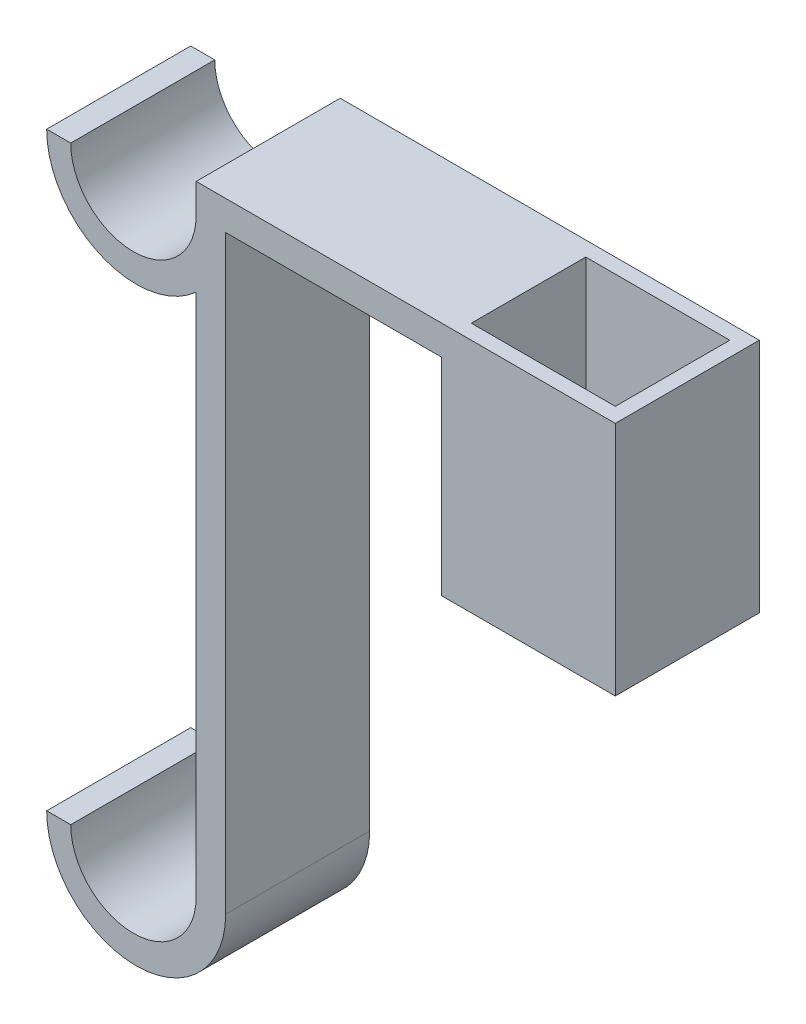
SolidWorks part; units mm, degrees
ref_plane "Front Plane" through (0, 0, 0) normal (0, 0, 1) x (1, 0, 0)
ref_plane "Top Plane" through (0, 0, 0) normal (0, 1, 0) x (1, 0, 0)
ref_plane "Right Plane" through (0, 0, 0) normal (1, 0, 0) x (0, 0, -1)
sketch "Sketch2" plane through (0, 0, 0) normal (0, 1, 0) x (1, 0, 0)
  line L1 (-14.7, -12.2) -> (14.7, -12.2)
  line L2 (-14.7, -12.2) -> (-14.7, 12.2)
  line L3 (-14.7, 12.2) -> (14.7, 12.2)
  line L4 (14.7, -12.2) -> (14.7, 12.2)
  line L5 (-14.7, -12.2) -> (14.7, 12.2) construction
  line L6 (-14.7, 12.2) -> (14.7, -12.2) construction
  point P0 (0, 0)
  dimension "D1" = 24.4
  dimension "D2" = 29.4
extrude "Boss-Extrude1" add sketch "Sketch2" along normal blind 35
sketch "Sketch4" plane through (0, 35, 0) normal (0, 1, 0) x (1, 0, 0)
  line L0 (-14.7, 12.2) -> (-44.5441, 12.2) construction
  line L2 (14.7, -12.2) -> (-56.3, -12.2)
  line L3 (14.7, -12.2) -> (14.7, 12.2)
  line L4 (14.7, 12.2) -> (-56.3, 12.2)
  line L5 (-56.3, -12.2) -> (-56.3, 12.2)
  dimension "D1" = 71
extrude "Boss-Extrude2" add sketch "Sketch4" along normal blind 5
sketch "Sketch5" plane through (0, 0, 12.2) normal (0, 0, 1) x (1, 0, 0)
  line L1 (-56.3, 35) -> (-51.3, 35)
  line L2 (-56.3, 35) -> (-56.3, -65)
  line L3 (-56.3, -65) -> (-51.3, -65)
  line L4 (-51.3, 35) -> (-51.3, -65)
  dimension "D1" = 5
  dimension "D2" = 100
extrude "Boss-Extrude3" add sketch "Sketch5" against normal up to surface (24.4 mm away) up to face at (-18.7667, 25, -12.2)
sketch "Sketch6" plane through (0, 0, 12.2) normal (0, 0, 1) x (1, 0, 0)
  line L0 (-81.625, -65) -> (-77.5512, -65)
  line L1 (-51.3, -65) -> (-81.625, -65) construction
  line L2 (-56.3, -65) -> (-51.3, -65)
  line L12 (-51.3, 35) -> (-56.3, 35) construction
  line L13 (-56.3, 40) -> (-56.3, -65) construction
  arc A0 (-51.3, -65) -> (-81.625, -65) centre (-66.4625, -65) cw
  arc A2 (-56.3, -65) -> (-77.5512, -65) centre (-66.9256, -65) cw
  line B0 (-81.625, 35) -> (-77.5512, 35)
  line B1 (-56.3, 35) -> (-51.3, 35)
  arc B2 (-51.3, 35) -> (-81.625, 35) centre (-66.4625, 35) cw
  arc B3 (-56.3, 35) -> (-77.5512, 35) centre (-66.9256, 35) cw
sketch_block_instance "Block1-1"
sketch_block "Block1"
sketch "Sketch7" plane through (0, 0, 12.2) normal (0, 0, 1) x (1, 0, 0)
  line L0 (-81.625, 35) -> (-77.5512, 35) construction
  line L1 (-56.3, 35) -> (-51.3, 35) construction
  line L2 (-51.3, -65) -> (-56.3, -65)
  line L3 (-77.5512, -65) -> (-81.625, -65)
  line L4 (-51.3, -65) -> (-56.3, -65)
  line L5 (-77.5512, -65) -> (-81.625, -65)
  line L6 (-81.625, 35) -> (-77.5512, 35)
  line L7 (-56.3, 35) -> (-51.3, 35)
  arc A0 (-77.5512, 35) -> (-56.3, 35) centre (-66.9256, 35) ccw construction
  arc A1 (-81.625, 35) -> (-51.3, 35) centre (-66.4625, 35) ccw construction
  arc A2 (-77.5512, -65) -> (-56.3, -65) centre (-66.9256, -65) ccw
  arc A3 (-81.625, -65) -> (-51.3, -65) centre (-66.4625, -65) ccw
  arc A4 (-77.5512, -65) -> (-56.3, -65) centre (-66.9256, -65) ccw
  arc A5 (-81.625, -65) -> (-51.3, -65) centre (-66.4625, -65) ccw
  arc A6 (-77.5512, 35) -> (-56.3, 35) centre (-66.9256, 35) ccw
  arc A7 (-81.625, 35) -> (-51.3, 35) centre (-66.4625, 35) ccw
  dimension "D1" = 0
extrude "Boss-Extrude5" add sketch "Sketch7" against normal up to surface (24.4 mm away) up to face at (-26.9, 2.5, -12.2)
sketch "Sketch3" plane through (0, 0, 0) normal (0, -1, 0) x (1, 0, 0)
  line L1 (-12.2, 9.7) -> (12.2, 9.7)
  line L2 (-12.2, 9.7) -> (-12.2, -9.7)
  line L3 (-12.2, -9.7) -> (12.2, -9.7)
  line L4 (12.2, 9.7) -> (12.2, -9.7)
  line L5 (-12.2, 9.7) -> (12.2, -9.7) construction
  line L6 (-12.2, -9.7) -> (12.2, 9.7) construction
  point P0 (0, 0)
  dimension "D1" = 24.4
  dimension "D2" = 19.4
extrude "Cut-Extrude1" cut sketch "Sketch3" against normal through all both and the other way through all
